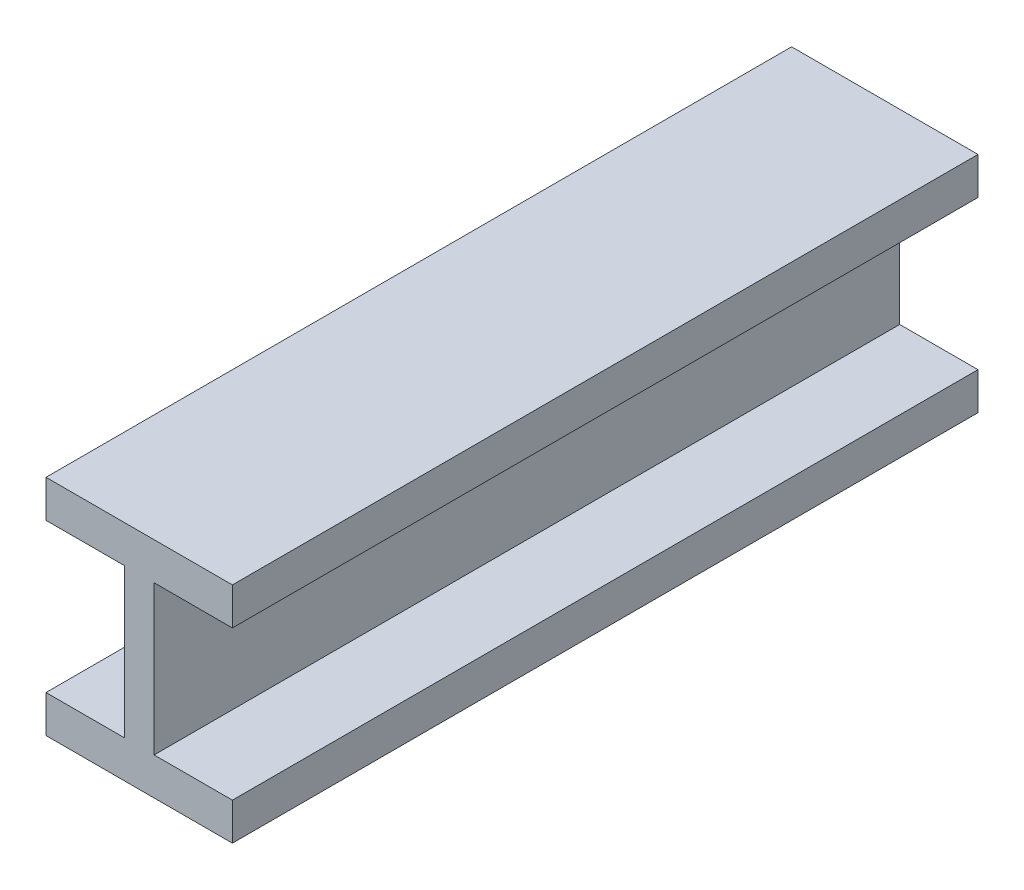
SolidWorks part; units mm, degrees
material "ABS P430"
ref_plane "Front Plane" through (0, 0, 0) normal (0, 0, 1) x (1, 0, 0)
ref_plane "Top Plane" through (0, 0, 0) normal (0, 1, 0) x (1, 0, 0)
ref_plane "Right Plane" through (0, 0, 0) normal (1, 0, 0) x (0, 0, -1)
sketch "Sketch3" plane through (0, 0, 0) normal (0, 1, 0) x (1, 0, 0)
  line L0 (0, 0) -> (0, 100.0652)
  point P3 (0, 50.0326)
  dimension "D1" = 100.0652
sketch "Sketch1" plane through (0, 0, 0) normal (0, 0, 1) x (1, 0, 0)
  line L1 (-12.5, -15) -> (12.5, -15)
  line L2 (-12.5, -15) -> (-12.5, 15)
  line L3 (-12.5, 15) -> (12.5, 15)
  line L4 (12.5, -15) -> (12.5, 15)
  line L5 (-12.5, -15) -> (12.5, 15) construction
  line L6 (-12.5, 15) -> (12.5, -15) construction
  line L7 (-12.5, -10) -> (12.5, -10)
  line L8 (-2, -10) -> (-2, 10)
  line L9 (-12.5, 10) -> (12.5, 10)
  line L10 (2, -10) -> (2, 10)
  line L11 (-2, -10) -> (2, 10) construction
  line L12 (-2, 10) -> (2, -10) construction
  point P0 (0, 0)
  point P6 (0, 0)
  dimension "D1" = 5
  dimension "D2" = 5
  dimension "D3" = 4
  dimension "D4" = 25
  dimension "D5" = 20
extrude "Boss-Extrude1" add sketch "Sketch1" against normal blind 100 contours L2 L9 L4 L3 | L7 L10 L9 L8 | L7 L2 L1 L4
ref_point "Point1" [suppressed]
equation "\"a\"= 25"
equation "\"b\"= 5"
equation "\"c\"= 20"
equation "\"d\"= 4"
equation "\"D1@Sketch1\"=\"b\""
equation "\"D2@Sketch1\"=\"b\""
equation "\"D5@Sketch1\"=\"c\""
equation "\"D3@Sketch1\"=\"d\""
equation "\"D4@Sketch1\"=\"a\""
equation "\"load\"= 20"
